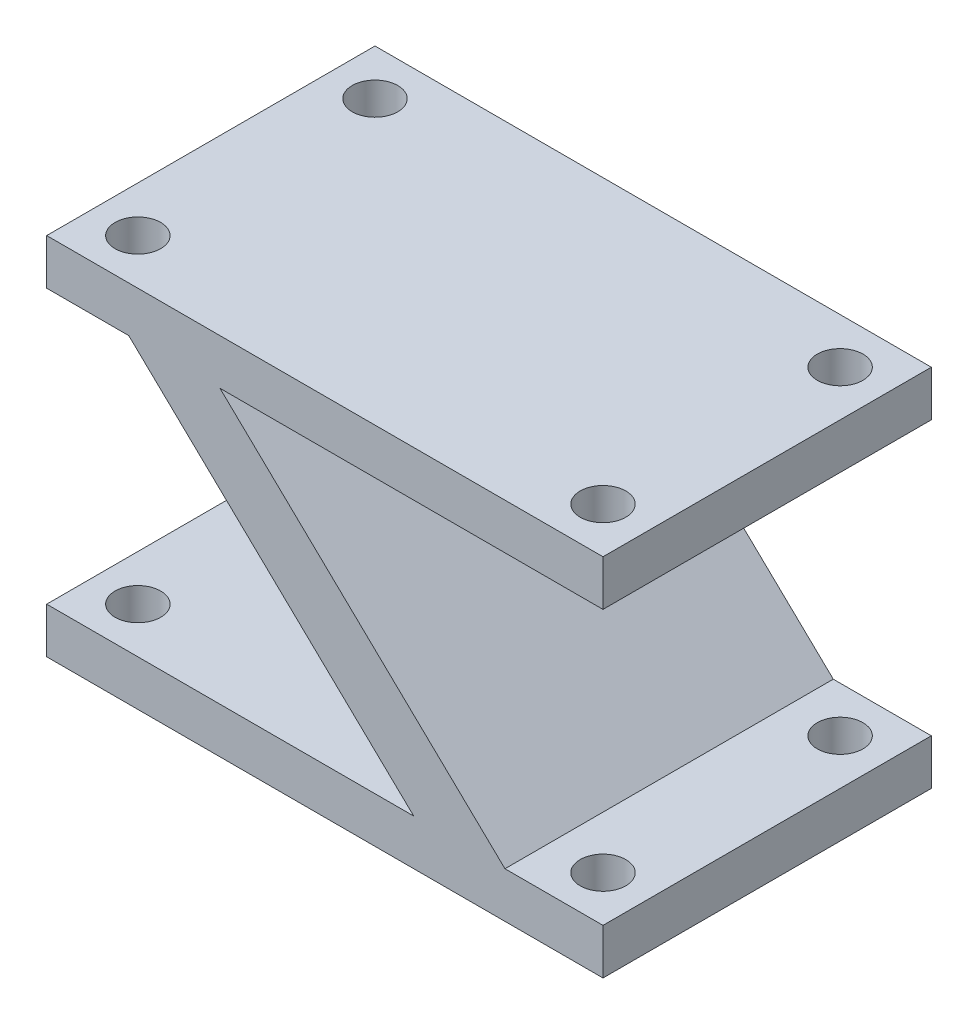
SolidWorks part; units mm, degrees
ref_plane "Front Plane" through (0, 0, 0) normal (0, 0, 1) x (1, 0, 0)
ref_plane "Top Plane" through (0, 0, 0) normal (0, 1, 0) x (1, 0, 0)
ref_plane "Right Plane" through (0, 0, 0) normal (1, 0, 0) x (0, 0, -1)
sketch "Sketch1" plane through (0, 0, 0) normal (0, 1, 0) x (1, 0, 0)
  line L1 (-30.5, -18) -> (30.5, -18)
  line L2 (-30.5, -18) -> (-30.5, 18)
  line L3 (-30.5, 18) -> (30.5, 18)
  line L4 (30.5, -18) -> (30.5, 18)
  line L5 (-30.5, -18) -> (30.5, 18) construction
  line L6 (-30.5, 18) -> (30.5, -18) construction
  circle A0 centre (-25.5, 13) radius 2.5
  circle A1 centre (25.5, 13) radius 2.5
  circle A2 centre (25.5, -13) radius 2.5
  circle A3 centre (-25.5, -13) radius 2.5
  point P0 (0, 0)
  point P8 (25.5, 13.6812)
  dimension "D3" = 5
  dimension "D1" = 36
  dimension "D2" = 61
  dimension "D4" = 5
  dimension "D5" = 26
  dimension "D8" = 5
  dimension "D9" = 5
  dimension "D6" = 2
  dimension "D7" = 2
extrude "Boss-Extrude1" add sketch "Sketch1" along normal blind 5
sketch "Sketch4" plane through (0, 0, 18) normal (0, 0, 1) x (1, 0, 0)
  line L0 (19.75, 5) -> (-11.5, 35)
  line L1 (-30.5, 5) -> (30.5, 5) construction
  line L2 (-11.5, 35) -> (-21.5, 35)
  line L3 (-21.5, 35) -> (9.75, 5)
  line L4 (9.75, 5) -> (19.75, 5)
  line L5 (30.5, 5) -> (30.5, 0) construction
  dimension "D1" = 30
  dimension "D2" = 10.75
  dimension "D3" = 20.75
  dimension "D4" = 52
extrude "Boss-Extrude3" add sketch "Sketch4" against normal up to surface (36 mm away) up to face at (0, 2.5, -18)
sketch "Sketch5" plane through (0, 35, 0) normal (0, 1, 0) x (1, 0, 0)
  line L1 (-30.5, -18) -> (30.5, -18)
  line L2 (-30.5, -18) -> (-30.5, 18)
  line L3 (-30.5, 18) -> (30.5, 18)
  line L4 (30.5, -18) -> (30.5, 18)
  circle A0 centre (-25.5, -13) radius 2.5
  circle A1 centre (-25.5, 13) radius 2.5
  circle A2 centre (25.5, 13) radius 2.5
  circle A3 centre (25.5, -13) radius 2.5
  dimension "D1" = 5
extrude "Boss-Extrude4" add sketch "Sketch5" along normal blind 5
